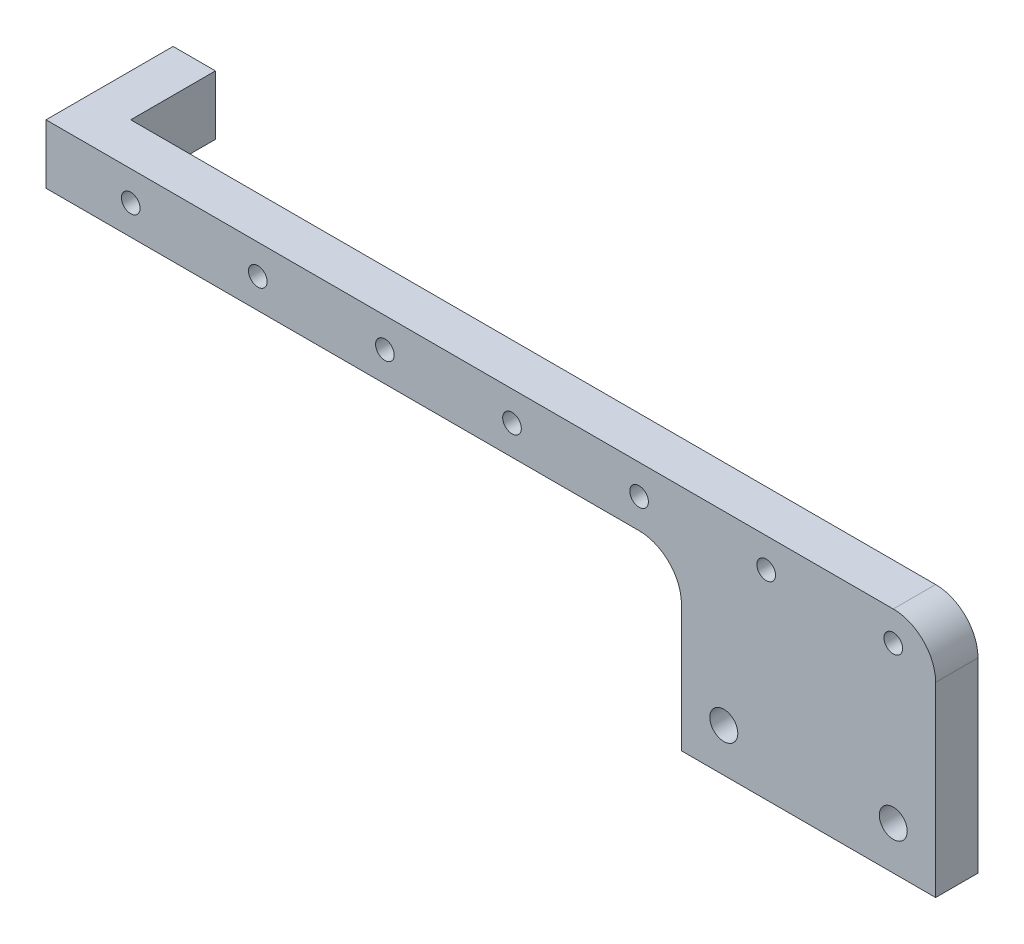
SolidWorks part; units mm, degrees
material "ABS"
ref_plane "前视基准面" through (0, 0, 0) normal (0, 0, 1) x (1, 0, 0)
ref_plane "上视基准面" through (0, 0, 0) normal (0, 1, 0) x (1, 0, 0)
ref_plane "右视基准面" through (0, 0, 0) normal (1, 0, 0) x (0, 0, -1)
sketch "草图1" plane through (0, 0, 0) normal (0, 0, 1) x (1, 0, 0)
  line L1 (0, 0) -> (100, 0)
  line L2 (0, 0) -> (0, 7)
  line L3 (0, 7) -> (100, 7)
  line L4 (100, 0) -> (100, 7)
  dimension "D1" = 100
  dimension "D2" = 7
extrude "凸台-拉伸1" add sketch "草图1" along normal blind 5 contours L2 L1 L4 L3
sketch "草图2" plane through (0, 0, 0) normal (0, 0, -1) x (-1, 0, 0)
  line L0 (-100, 3.5) -> (0, 3.5) construction
  line L1 (-100, 0) -> (-100, 7) construction
  line L2 (0, 0) -> (0, 7) construction
  circle A0 centre (-95, 3.5) radius 1.1
  circle A1 centre (-80, 3.5) radius 1.1
  circle A2 centre (-65, 3.5) radius 1.1
  circle A3 centre (-50, 3.5) radius 1.1
  circle A4 centre (-35, 3.5) radius 1.1
  circle A5 centre (-20, 3.5) radius 1.1
  circle A6 centre (-5, 3.5) radius 1.1
  dimension "D1" = 2.2
  dimension "D2" = 5
  dimension "D4" = 15
  dimension "D3" = 7
extrude "切除-拉伸1" cut sketch "草图2" against normal through all
sketch "草图3" plane through (0, 0, 0) normal (0, 0, -1) x (-1, 0, 0)
  line L1 (-100, 0) -> (-70, 0)
  line L2 (-100, 0) -> (-100, -20)
  line L3 (-100, -20) -> (-70, -20)
  line L4 (-70, 0) -> (-70, -20)
  dimension "D1" = 30
  dimension "D2" = 20
extrude "凸台-拉伸2" add sketch "草图3" against normal blind 5
sketch "草图4" plane through (0, 0, 5) normal (0, 0, 1) x (1, 0, 0)
  line L0 (0, 7) -> (100, 7) construction
  line L1 (0, 0) -> (-5, 0)
  line L2 (0, 0) -> (0, 7)
  line L3 (0, 7) -> (-5, 7)
  line L4 (-5, 0) -> (-5, 7)
  dimension "D1" = 5
extrude "凸台-拉伸3" add sketch "草图4" against normal blind 15
sketch "草图5" plane through (0, 0, 0) normal (0, 0, -1) x (-1, 0, 0)
  line L0 (-100, -14.9) -> (-70, -14.9) construction
  line L1 (-100, -20) -> (-100, 7) construction
  line L2 (-70, -20) -> (-70, 0) construction
  line L3 (-100, -20) -> (-70, -20) construction
  circle A0 centre (-95, -14.9) radius 1.65
  circle A1 centre (-75, -14.9) radius 1.65
  dimension "D2" = 3.3
  dimension "D1" = 5.1
  dimension "D3" = 5
  dimension "D4" = 5
extrude "切除-拉伸2" cut sketch "草图5" against normal blind 15
fillet "圆角1" radius 5 2 edges at (70, 0, 2.5) (100, 7, 2.5)
